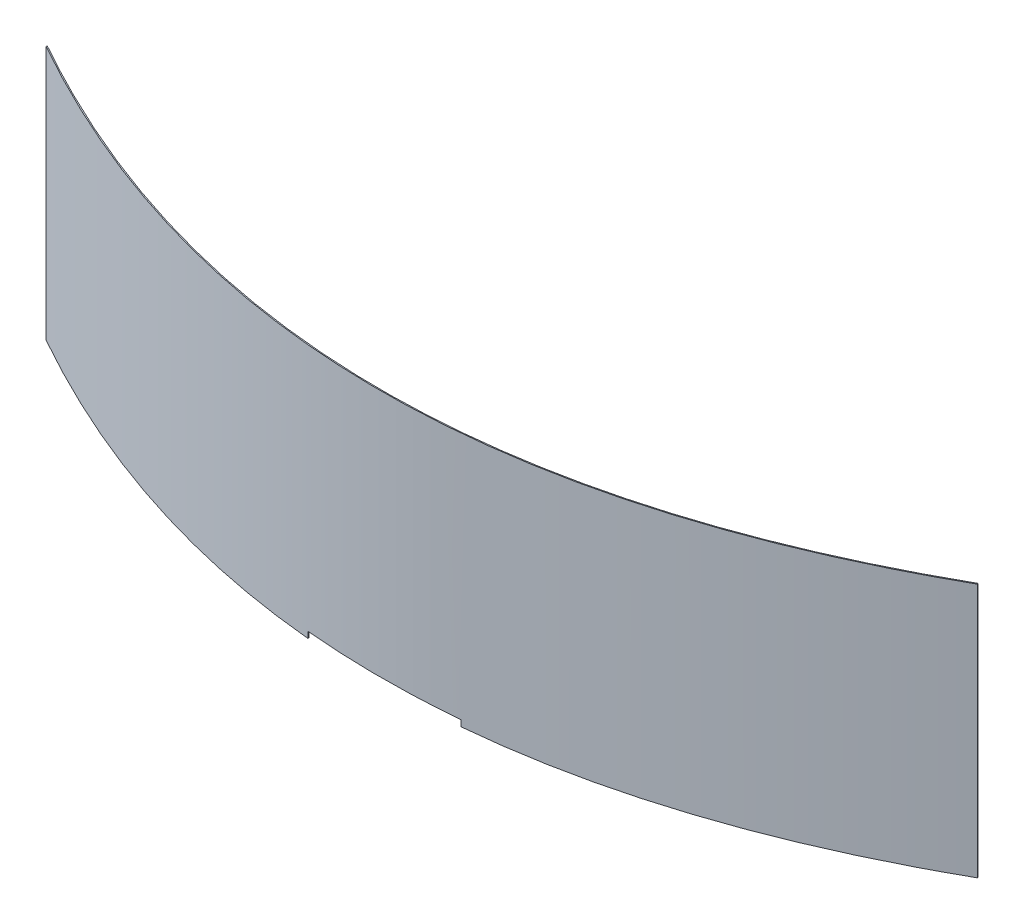
SolidWorks part; units mm, degrees
ref_plane "Front Plane" through (0, 0, 0) normal (0, 0, 1) x (1, 0, 0)
ref_plane "Top Plane" through (0, 0, 0) normal (0, 1, 0) x (1, 0, 0)
ref_plane "Right Plane" through (0, 0, 0) normal (1, 0, 0) x (0, 0, -1)
sketch "Sketch1" plane through (0, 0, 0) normal (0, 1, 0) x (1, 0, 0)
  line L0 (0, -200) -> (0, 0) construction
  line L1 (-225, -136.7187) -> (225, -136.7187) construction
  line L4 (-225, -136.7187) -> (-225.2451, -137.1545)
  line L5 (225.2451, -137.1545) -> (225, -136.7187)
  parabola Q0 (-225, -136.7187) -> (225, -136.7187) focus (0, 0) apex (0, -200)
  spline S0 degree 1 poles (-225.2451, -137.1545) (225.2451, -137.1545) knots 0 0 1 1 construction
  spline S1 degree 3 poles (-225.2451, -137.1545) (-222.9082, -138.4691) (-218.2041, -141.0739) (-208.8273, -146.1009) (-197.0951, -152.0818) (-183.0206, -158.7616) (-164.2523, -167.0094) (-140.7912, -176.0823) (-112.6357, -184.9909) (-84.4784, -191.9202) (-46.9336, -198.52) (0, -201.82) (46.9336, -198.52) (84.4784, -191.9202) (112.6357, -184.9909) (140.7912, -176.0823) (164.2523, -167.0094) (183.0206, -158.7616) (197.0951, -152.0818) (208.8273, -146.1009) (218.2041, -141.0739) (222.9082, -138.4691) (225.2451, -137.1545) knots 0.496023 0.496023 0.496023 0.496023 0.496147 0.496271 0.49652 0.496768 0.497017 0.497514 0.498011 0.498508 0.499006 0.5 0.500994 0.501492 0.501989 0.502486 0.502983 0.503232 0.50348 0.503729 0.503853 0.503977 0.503977 0.503977 0.503977
  dimension "D2" = 200
  dimension "D3" = 0.5
extrude "Boss-Extrude1" add sketch "Sketch1" along normal blind 123
sketch "Sketch2" plane through (0, 0, 0) normal (0, 0, 1) x (1, 0, 0)
  line L0 (-225, 0) -> (225, 0) construction
  line L1 (37, 3) -> (-37, 3)
  line L2 (37, 3) -> (37, 0)
  line L3 (37, 0) -> (-37, 0)
  line L4 (-37, 3) -> (-37, 0)
  point P4 (0, 0)
  point P7 (0, 0)
  dimension "D1" = 74
  dimension "D2" = 3
extrude "Cut-Extrude1" cut sketch "Sketch2" along normal up to surface (198.7909 mm away)
